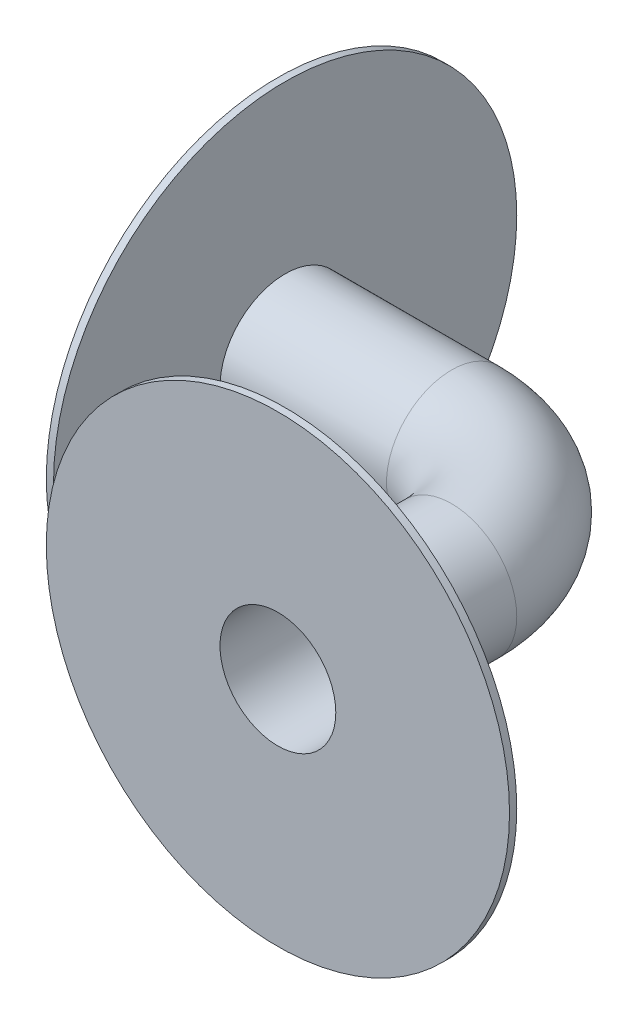
SolidWorks part; units mm, degrees
material "Copper"
ref_plane "Front Plane" through (0, 0, 0) normal (0, 0, 1) x (1, 0, 0)
ref_plane "Top Plane" through (0, 0, 0) normal (0, 1, 0) x (1, 0, 0)
ref_plane "Right Plane" through (0, 0, 0) normal (1, 0, 0) x (0, 0, -1)
sketch "Sketch1" plane through (0, 0, 0) normal (1, 0, 0) x (0, 0, -1)
  line L0 (-25.4, 0) -> (-25.4, 30.1607) construction
  circle A0 centre (0, 0) radius 12.7
  circle A1 centre (0, 0) radius 14.2875
  dimension "D1" = 25.4
  dimension "D2" = 28.575
  dimension "D3" = 25.4
revolve "Revolve1" add sketch "Sketch1" angle 90 about L0
sketch "Sketch2" plane through (0, 0, 25.4) normal (0, 0, 1) x (1, 0, 0)
  circle A0 centre (25.4, 0) radius 12.7 construction
  circle A1 centre (25.4, 0) radius 14.2875
  circle A2 centre (25.4, 0) radius 14.2875
  circle A3 centre (25.4, 0) radius 12.7
  dimension "D1" = 0
extrude "Boss-Extrude1" add sketch "Sketch2" along normal blind 38.1
sketch "Sketch3" plane through (0, 0, 0) normal (-1, 0, 0) x (0, 0, 1)
  circle A0 centre (0, 0) radius 12.7 construction
  circle A1 centre (0, 0) radius 14.2875
  circle A2 centre (0, 0) radius 14.2875
  circle A3 centre (0, 0) radius 12.7
  dimension "D1" = 0
extrude "Boss-Extrude2" add sketch "Sketch3" along normal blind 38.1
sketch "Sketch4" plane through (-38.1, 0, 0) normal (-1, 0, 0) x (0, 0, 1)
  circle A0 centre (0, 0) radius 12.7 construction
  circle A1 centre (0, 0) radius 12.7
  circle A2 centre (0, 0) radius 50.8
  dimension "D1" = 101.6
extrude "Boss-Extrude3" add sketch "Sketch4" against normal blind 1.5875
sketch "Sketch5" plane through (0, 0, 63.5) normal (0, 0, 1) x (1, 0, 0)
  circle A0 centre (25.4, 0) radius 12.7 construction
  circle A1 centre (25.4, 0) radius 12.7
  circle A2 centre (25.4, 0) radius 50.8
  dimension "D1" = 101.6
extrude "Boss-Extrude4" add sketch "Sketch5" against normal blind 1.5875
